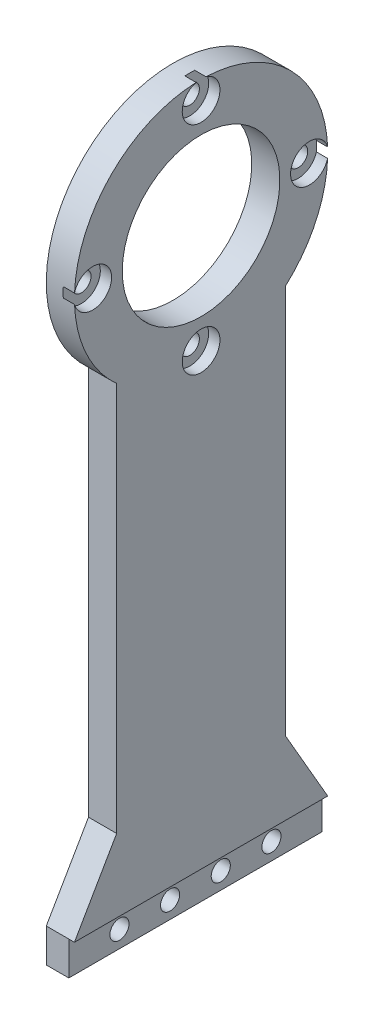
SolidWorks part; units mm, degrees
material "Сплав 2024"
ref_plane "Спереди" through (0, 0, 0) normal (0, 0, 1) x (1, 0, 0)
ref_plane "Сверху" through (0, 0, 0) normal (0, 1, 0) x (1, 0, 0)
ref_plane "Справа" through (0, 0, 0) normal (1, 0, 0) x (0, 0, -1)
sketch "Эскиз1" plane through (0, 0, 0) normal (0, 1, 0) x (1, 0, 0)
  line L1 (0, 0) -> (5, 0)
  line L2 (0, 0) -> (0, -30)
  line L3 (0, -30) -> (5, -30)
  line L4 (5, 0) -> (5, -30)
  dimension "D1" = 5
  dimension "D2" = 30
extrude "Бобышка-Вытянуть1" add sketch "Эскиз1" along normal blind 227
sketch "Эскиз2" plane through (0, 0, 0) normal (-1, 0, 0) x (0, 0, 1)
  line L0 (30, 105) -> (0, 105) construction
  line L3 (15, 227) -> (15, 0) construction
  line L4 (0, 227) -> (30, 227) construction
  line L5 (0, 0) -> (30, 0) construction
  line L6 (30, 0) -> (0, 0) construction
  circle A0 centre (15, 105) radius 22.5
  dimension "D1" = 45
  dimension "D2" = 105
extrude "Бобышка-Вытянуть2" add sketch "Эскиз2" against normal up to surface (5 mm away) up to face at (5, 113.5, 15)
sketch "Эскиз3" plane through (0, 0, 0) normal (-1, 0, 0) x (0, 0, 1)
  circle A0 centre (15, 105) radius 14
  dimension "D1" = 28
extrude "Вырез-Вытянуть1" cut sketch "Эскиз3" against normal through all
sketch "Эскиз4" plane through (5, 0, 0) normal (-1, 0, 0) x (0, 0, 1)
  line L0 (15, 127.5) -> (15, 82.5) construction
  line L1 (15, 227) -> (15, 0) construction
  line L2 (37.5, 105) -> (-7.5, 105) construction
  circle A0 centre (15, 105) radius 19.25 construction
  circle A1 centre (15, 105) radius 22.5 construction
  dimension "D1" = 38.5
hole_wizard "Цековка для  винта с полукруглой головкой M31" positions "Эскиз6" profile "Эскиз5" counterbore size "M3" standard "Ansi Metric" end condition through all
sketch "Эскиз6" plane through (5, -25.0247, 7.2629) normal (-1, 0, 0) x (0, 0, 1)
  line L0 (7.7371, 152.5247) -> (7.7371, 107.5247) construction
  line L1 (30.2371, 130.0247) -> (-14.7629, 130.0247) construction
  circle A0 centre (7.7371, 130.0247) radius 19.25 construction
  point P0 (7.7371, 149.2747)
  point P6 (-11.5129, 130.0247)
  point P10 (7.7371, 110.7747)
  point P12 (26.9871, 130.0247)
sketch "Эскиз5" plane through (5, 124.25, 15) normal (0, 1, 0) x (0, 0, -1)
  line L0 (0, 0) -> (0, 5)
  line L1 (0, 5) -> (1.7, 5)
  line L3 (1.7, 5) -> (1.7, 2)
  line L4 (1.7, 2) -> (3.35, 2)
  line L5 (3.35, 2) -> (3.35, 0)
  line L7 (3.35, 0) -> (0, 0)
  line L11 (0, -6.35) -> (0, 107.95) construction
  dimension "Диаметр сквозного отверстия" = 3.4
  dimension "Глубина сквозного отверстия" = 5
  dimension "Диаметр цековки" = 6.7
  dimension "Глубина цековки" = 2
sketch "Эскиз8" plane through (5, 0, 0) normal (1, 0, 0) x (0, 0, -1)
  line L0 (-15, 227) -> (-15, 0) construction
  line L1 (-30, 227) -> (0, 227) construction
  line L2 (-30, 0) -> (0, 0) construction
  line L3 (19.447, 105) -> (-49.447, 105) construction
  line L4 (0, 227) -> (0, 121.7705) construction
  line L5 (-26, 145) -> (-4, 145) construction
  line L6 (-26, 145) -> (-26, 65) construction
  line L7 (-26, 65) -> (-4, 65) construction
  line L8 (-4, 145) -> (-4, 65) construction
  line L9 (-26, 145) -> (-4, 65) construction
  line L10 (-26, 65) -> (-4, 145) construction
  point P8 (-15, 105)
  point P9 (-15, 105)
  dimension "D1" = 4
  dimension "D2" = 80
  dimension "D3" = 105
sketch "Эскиз11" plane through (5, 0, 0) normal (1, 0, 0) x (0, 0, -1)
  line L0 (-30, 0) -> (0, 0) construction
  line L1 (-15, 227) -> (-15, 0) construction
  line L2 (-30, 227) -> (0, 227) construction
  line L3 (0, 88.2295) -> (0, 0) construction
  line L4 (-30, 88.2295) -> (-30, 0) construction
  line L5 (-37.5, 3) -> (7.5, 3) construction
  line L20 (-1.5, 0) -> (-1.5, 6) construction
  line L21 (-10.5, 0) -> (-10.5, 6) construction
  line L22 (-19.5, 0) -> (-19.5, 6) construction
  line L23 (-28.5, 0) -> (-28.5, 6) construction
  line L25 (-37.5, 0) -> (7.5, 6) construction
  line L26 (-37.5, 6) -> (7.5, 0) construction
  line L27 (-37.5, 6) -> (7.5, 6) construction
  line L28 (0, 18.9904) -> (7.5, 6)
  line L29 (-30, 18.9904) -> (0, 18.9904)
  line L30 (7.5, 6) -> (7.5, 0)
  line L31 (-37.5, 0) -> (7.5, 0)
  line L32 (-37.5, 6) -> (-37.5, 0)
  line L33 (-37.5, 6) -> (-30, 18.9904)
  point P2 (-15, 3)
  dimension "D1" = 45
  dimension "D2" = 6
  dimension "D3" = 9
  dimension "D4" = 9
  dimension "D5" = 9
  dimension "D6" = 9
  dimension "D7" = 120
extrude "Бобышка-Вытянуть3" add sketch "Эскиз11" against normal up to surface (5 mm away) up to face at (0, 124.25, 13.3)
hole_wizard "Отверстие с зазором M31" positions "Эскиз13" profile "Эскиз12" hole size "M3" standard "Ansi Metric" end condition through all
sketch "Эскиз13" plane through (5, 0, 0) normal (1, 0, 0) x (0, 0, -1)
  line L4 (-28.5, 0) -> (-28.5, 6) construction
  line L5 (-19.5, 0) -> (-19.5, 6) construction
  line L6 (-10.5, 0) -> (-10.5, 6) construction
  line L7 (-1.5, 0) -> (-1.5, 6) construction
  point P16 (-28.5, 3)
  point P20 (-19.5, 3)
  point P24 (-10.5, 3)
  point P28 (-1.5, 3)
sketch "Эскиз12" plane through (5, 3, 28.5) normal (0, 1, 0) x (0, 0, -1)
  line L0 (0, 0) -> (0, 5)
  line L1 (0, 5) -> (1.7, 5)
  line L2 (1.7, 5) -> (1.7, 0)
  line L5 (1.7, 0) -> (0, 0)
  line L11 (0, -6.35) -> (0, 107.95) construction
  dimension "Диаметр сквозного отверстия" = 3.4
  dimension "Глубина сквозного отверстия" = 5
sketch "Эскиз14" plane through (5, 0, 0) normal (1, 0, 0) x (0, 0, -1)
  line L5 (-37.5, 0) -> (7.5, 0)
  line L6 (-37.5, 0) -> (-37.5, 6)
  line L7 (-37.5, 6) -> (7.5, 6)
  line L8 (7.5, 0) -> (7.5, 6)
extrude "Вырез-Вытянуть2" cut sketch "Эскиз14" against normal blind 1
sketch "Эскиз15" plane through (5, 0, 0) normal (1, 0, 0) x (0, 0, -1)
  line L0 (0, 227) -> (0, 121.7705) construction
  line L1 (-30, 227) -> (0, 227)
  line L2 (-30, 227) -> (-30, 121.7705)
  line L4 (0, 227) -> (0, 121.7705)
  arc A1 (-30, 121.7705) -> (0, 121.7705) centre (-15, 105) cw
extrude "Вырез-Вытянуть3" cut sketch "Эскиз15" against normal up to surface (5 mm away) up to face at (0, 3, 26.8)
equation "\"D4@Эскиз11\"=\"D3@Эскиз11\""
equation "\"D5@Эскиз11\"=\"D3@Эскиз11\""
equation "\"D6@Эскиз11\"=\"D4@Эскиз11\""
equation "\"D3@Эскиз11\" = \"D1@Эскиз11\" / 5"
